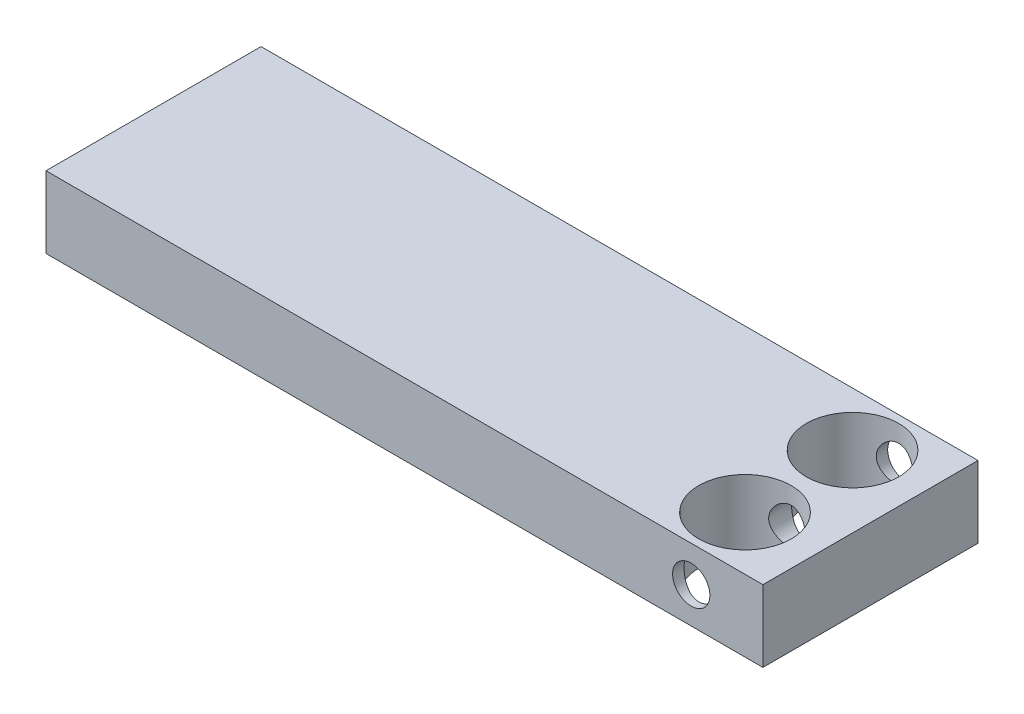
SolidWorks part; units mm, degrees
ref_plane "Front Plane" through (0, 0, 0) normal (0, 0, 1) x (1, 0, 0)
ref_plane "Top Plane" through (0, 0, 0) normal (0, 1, 0) x (1, 0, 0)
ref_plane "Right Plane" through (0, 0, 0) normal (1, 0, 0) x (0, 0, -1)
sketch "Sketch1" plane through (0, 0, 0) normal (0, 1, 0) x (1, 0, 0)
  line L1 (-24.8109, 19.0696) -> (75.1891, 19.0696)
  line L2 (-24.8109, 19.0696) -> (-24.8109, -10.9304)
  line L3 (-24.8109, -10.9304) -> (75.1891, -10.9304)
  line L4 (75.1891, 19.0696) -> (75.1891, -10.9304)
  circle A0 centre (65.1891, 11.5696) radius 6.45
  circle A1 centre (65.1891, -3.4304) radius 6.45
  dimension "D2" = 12.9
  dimension "D4" = 12.9
  dimension "D1" = 100
  dimension "D3" = 30
  dimension "D5" = 15
  dimension "D6" = 7.5
  dimension "D7" = 10
extrude "Boss-Extrude1" add sketch "Sketch1" along normal blind 10
sketch "Sketch2" plane through (0, 0, 10.9304) normal (0, 0, 1) x (1, 0, 0)
  line L0 (-24.8109, 10) -> (75.1891, 10) construction
  line L1 (75.1891, 10) -> (75.1891, 0) construction
  circle A0 centre (65.1891, 5) radius 2.6
  dimension "D1" = 5
  dimension "D2" = 10
extrude "Cut-Extrude1" cut sketch "Sketch2" against normal through all
